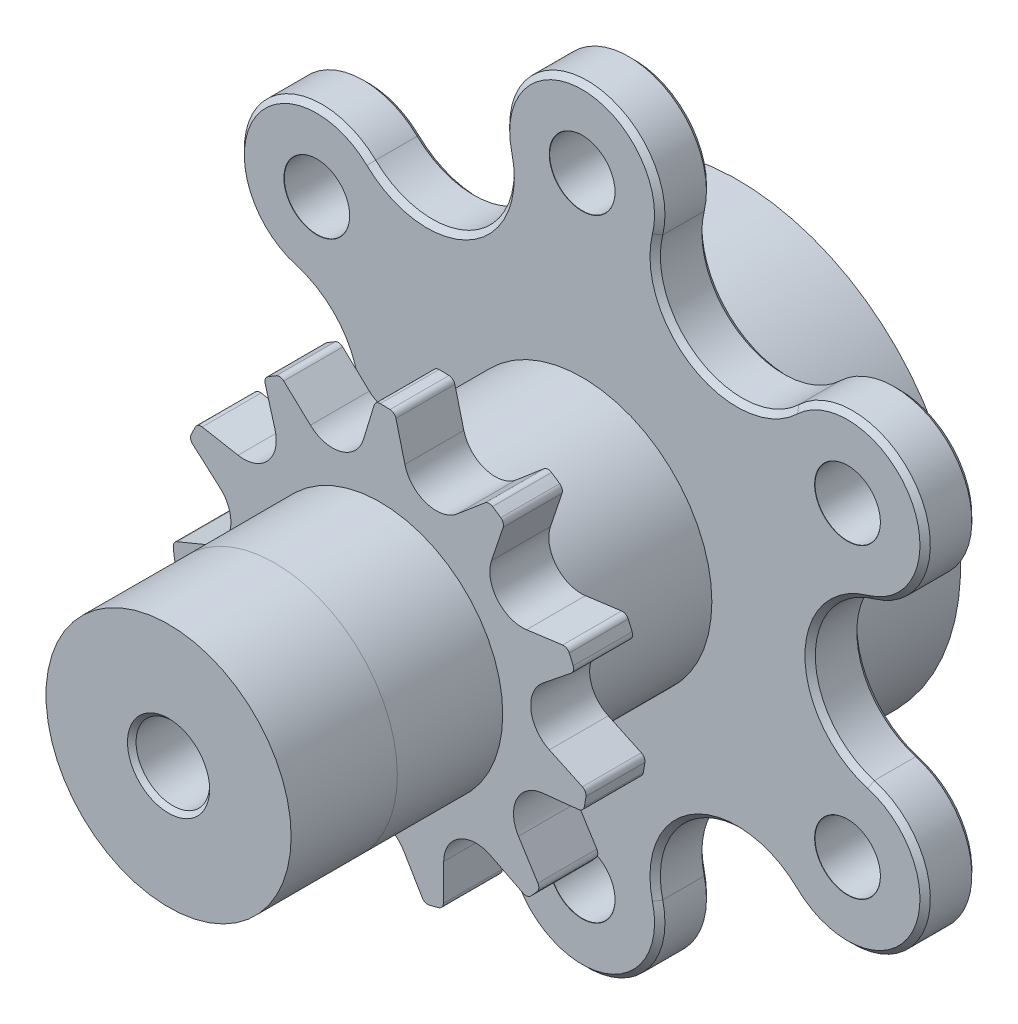
SolidWorks part; units mm, degrees
material "AISI 4130 Steel, annealed at 865C"
ref_plane "Front Plane" through (0, 0, 0) normal (0, 0, 1) x (1, 0, 0)
ref_plane "Top Plane" through (0, 0, 0) normal (0, 1, 0) x (1, 0, 0)
ref_plane "Right Plane" through (0, 0, 0) normal (1, 0, 0) x (0, 0, -1)
sketch "Sketch1" plane through (0, 0, 0) normal (0, 0, 1) x (1, 0, 0)
  circle A0 centre (0, 0) radius 47
  dimension "D1" = 94
extrude "Boss-Extrude1" add sketch "Sketch1" along normal blind 6.35
hole_wizard "Ø8.0mm Dowel Hole1" positions "Sketch3" profile "Sketch4" hole size "Ø8.0" standard "ANSI Metric" end condition through all
sketch "Sketch3" plane through (0, 0, 6.35) normal (0, 0, 1) x (1, 0, 0)
  point P0 (0, -37.5)
  dimension "D1" = 37.5
sketch "Sketch4" plane through (0, -37.5, 6.35) normal (1, 0, 0) x (0, -1, 0)
  line L0 (0, 0) -> (0, 6.35)
  line L1 (0, 6.35) -> (4, 6.35)
  line L2 (4, 6.35) -> (4, 0.025)
  line L3 (4, 0.025) -> (4.025, 0)
  line L5 (4.025, 0) -> (0, 0)
  line L6 (-4, 0.025) -> (-4.025, 0) construction
  line L11 (0, -6.35) -> (0, 107.95) construction
  dimension "Thru Hole Dia." = 8
  dimension "Thru Hole Depth" = 6.35
  dimension "Near C'Sink Dia." = 8.05
  dimension "Near C'Sink Angle" = 90
pattern_circular "CirPattern1" count 6 over 360 about axis through (0, 0, 0) along (0, 0, 1) of "Ø8.0mm Dowel Hole1"
sketch "Sketch5" plane through (0, 0, 6.35) normal (0, 0, 1) x (1, 0, 0)
  circle A0 centre (0, -37.5) radius 9.5 construction
  circle A1 centre (0, 0) radius 47 construction
  circle A2 centre (0, 0) radius 47
  circle A3 centre (-32.476, -18.75) radius 9.5 construction
  circle A4 centre (-32.476, 18.75) radius 9.5 construction
  circle A5 centre (0, 37.5) radius 9.5 construction
  circle A6 centre (32.476, 18.75) radius 9.5 construction
  circle A7 centre (32.476, -18.75) radius 9.5 construction
  circle A8 centre (0, 0) radius 27.9 construction
  arc A9 (-25.9015, 25.6076) -> (-9.2261, 35.2352) centre (-18.963, 32.8449) ccw
  arc A10 (9.2261, 35.2352) -> (25.9015, 25.6076) centre (18.963, 32.8449) ccw
  arc A11 (35.1276, 9.6276) -> (35.1276, -9.6276) centre (37.926, 0) ccw
  arc A12 (25.9015, -25.6076) -> (9.2261, -35.2352) centre (18.963, -32.8449) ccw
  arc A13 (-9.2261, -35.2352) -> (-25.9015, -25.6076) centre (-18.963, -32.8449) ccw
  arc A14 (-35.1276, -9.6276) -> (-35.1276, 9.6276) centre (-37.926, 0) ccw
  arc A15 (-9.2261, 35.2352) -> (9.2261, 35.2352) centre (0, 37.5) cw
  arc A16 (-25.9015, 25.6076) -> (-35.1276, 9.6276) centre (-32.476, 18.75) ccw
  arc A17 (-35.1276, -9.6276) -> (-25.9015, -25.6076) centre (-32.476, -18.75) ccw
  arc A18 (-9.2261, -35.2352) -> (9.2261, -35.2352) centre (0, -37.5) ccw
  arc A19 (25.9015, -25.6076) -> (35.1276, -9.6276) centre (32.476, -18.75) ccw
  arc A20 (25.9015, 25.6076) -> (35.1276, 9.6276) centre (32.476, 18.75) cw
  point P19 (0, 0)
  point P38 (0, 0)
  circle M13 centre (0, 0) radius 47
  dimension "D1" = 6
  dimension "D2" = 55.8
  dimension "D3" = 6
extrude "Cut-Extrude1" cut sketch "Sketch5" against normal through all contours A16 A9 A15 M13 | A10 A20 A2 A15 | A17 A14 A16 A2 | A18 A13 A17 M13 | A19 A12 A18 A2 | A20 A11 A19 M13
chamfer "Chamfer1" distance 0.635 angle 45 24 edges at (-40.7032, 23.5, 6.35) (-27.9, 0, 6.35) (-40.7032, -23.5, 6.35) (-13.95, -24.1621, 6.35) (0, -47, 6.35) (13.95, -24.1621, 6.35) (40.7032, -23.5, 6.35) (27.9, 0, 6.35) (40.7032, 23.5, 6.35) (13.95, 24.1621, 6.35) (0, 47, 6.35) (-13.95, 24.1621, 6.35) (0, -47, 0) (-13.95, -24.1621, 0) (13.95, -24.1621, 0) (-40.7032, -23.5, 0) (40.7032, -23.5, 0) (-27.9, 0, 0) (27.9, 0, 0) (-40.7032, 23.5, 0) (40.7032, 23.5, 0) (-13.95, 24.1621, 0) (13.95, 24.1621, 0) (0, 47, 0)
sketch "Sketch6" [suppressed] plane through (0, 0, 6.35) normal (0, 0, 1) x (1, 0, 0)
  circle A0 centre (0, 0) radius 15.875
  dimension "D1" = 31.75
extrude "Shaft" [suppressed] add sketch "Sketch6" along normal blind 53.848
sketch "Sketch7" [suppressed] plane through (0, 0, 60.198) normal (0, 0, 1) x (1, 0, 0)
  arc A0 (9.097, -5.6181) -> (9.7313, -4.4292) centre (0, 0) ccw
  arc A1 (9.097, -5.6181) -> (9.0986, -5.9863) centre (9.3955, -5.8008) ccw
  arc A2 (10.055, -4.164) -> (9.7313, -4.4292) centre (10.071, -4.5136) ccw
  arc A3 (12.1705, -3.6562) -> (12.3739, -3.4251) centre (12.0362, -3.333) ccw
  arc A4 (12.3739, -3.4251) -> (12.5248, -2.8127) centre (0.0056, -0.0518) ccw
  arc A5 (9.3895, -8.7865) -> (9.8078, -8.3144) centre (0.0056, -0.0518) ccw
  arc A6 (4.2554, -12.1469) -> (4.8452, -11.9232) centre (0.0056, -0.0518) ccw
  arc A7 (-1.8522, -12.7365) -> (-1.2261, -12.8125) centre (0.0056, -0.0518) ccw
  arc A8 (-7.5343, -10.4201) -> (-7.0152, -10.7784) centre (0.0056, -0.0518) ccw
  arc A9 (-11.489, -5.7285) -> (-11.1959, -6.287) centre (0.0056, -0.0518) ccw
  arc A10 (-12.8144, -0.0518) -> (-12.8105, -0.3671) centre (0.0056, -0.0518) ccw
  arc A11 (12.533, -2.7373) -> (12.4521, -2.5135) centre (12.183, -2.7373) ccw
  arc A12 (12.5248, -2.8127) -> (12.533, -2.7373) centre (12.183, -2.7373) ccw
  arc A13 (10.6424, -0.7555) -> (10.815, -1.0808) centre (10.9916, -0.7786) ccw
  arc A14 (10.6424, -0.7555) -> (10.6656, -0.0518) centre (0.0056, -0.0518) ccw
  arc A15 (10.6656, -0.0518) -> (10.6424, 0.6519) centre (0.0056, -0.0518) ccw
  arc A16 (10.815, 0.9772) -> (10.6424, 0.6519) centre (10.9916, 0.6751) ccw
  arc A17 (12.4521, 2.41) -> (12.533, 2.6337) centre (12.183, 2.6337) ccw
  arc A18 (-12.8105, 0.2636) -> (-12.8144, -0.0518) centre (0.0056, -0.0518) ccw
  arc A19 (-11.1959, 6.1834) -> (-11.489, 5.6249) centre (0.0056, -0.0518) ccw
  arc A20 (-7.0152, 10.6748) -> (-7.5343, 10.3165) centre (0.0056, -0.0518) ccw
  arc A21 (-1.2261, 12.7089) -> (-1.8522, 12.6329) centre (0.0056, -0.0518) ccw
  arc A22 (4.8452, 11.8197) -> (4.2554, 12.0433) centre (0.0056, -0.0518) ccw
  arc A23 (9.8078, 8.2108) -> (9.3895, 8.6829) centre (0.0056, -0.0518) ccw
  arc A24 (12.5248, 2.7091) -> (12.3739, 3.3215) centre (0.0056, -0.0518) ccw
  arc A25 (12.533, 2.6337) -> (12.5248, 2.7091) centre (12.183, 2.6337) ccw
  arc A26 (12.3739, 3.3215) -> (12.1705, 3.5526) centre (12.0362, 3.2294) ccw
  arc A27 (9.751, 4.2682) -> (10.055, 4.0604) centre (10.071, 4.4101) ccw
  arc A28 (9.751, 4.2682) -> (9.097, 5.5145) centre (0.0056, -0.0518) ccw
  arc A29 (9.0986, 5.8827) -> (9.097, 5.5145) centre (9.3955, 5.6972) ccw
  arc A30 (9.8901, 7.9852) -> (9.8078, 8.2108) centre (9.5401, 7.9852) ccw
  arc A31 (9.8824, 7.9122) -> (9.8901, 7.9852) centre (9.5401, 7.9852) ccw
  arc A32 (9.3895, 8.6829) -> (9.102, 8.793) centre (9.1333, 8.4444) ccw
  arc A33 (6.6272, 8.3023) -> (5.4688, 9.1018) centre (0.0056, -0.0518) ccw
  arc A34 (6.6272, 8.3023) -> (6.9929, 8.2596) centre (6.8446, 8.5766) ccw
  arc A35 (5.2992, 9.4287) -> (5.4688, 9.1018) centre (5.6482, 9.4024) ccw
  arc A36 (5.0501, 11.5899) -> (4.8452, 11.8197) centre (4.713, 11.4956) ccw
  arc A37 (4.2554, 12.0433) -> (3.9497, 12.0072) centre (4.1394, 11.7131) ccw
  arc A38 (1.9864, 10.4226) -> (0.5891, 10.5922) centre (0.0056, -0.0518) ccw
  arc A39 (1.9864, 10.4226) -> (2.3301, 10.5547) centre (2.0514, 10.7665) ccw
  arc A40 (0.2871, 10.8028) -> (0.5891, 10.5922) centre (0.6083, 10.9417) ccw
  arc A41 (-0.9379, 12.6007) -> (-1.2261, 12.7089) centre (-1.1925, 12.3605) ccw
  arc A42 (-1.8522, 12.6329) -> (-2.1062, 12.4588) centre (-1.8015, 12.2866) ccw
  arc A43 (-3.1082, 10.1433) -> (-4.4242, 9.6442) centre (0.0056, -0.0518) ccw
  arc A44 (-3.1082, 10.1433) -> (-2.8653, 10.42) centre (-3.2104, 10.478) ccw
  arc A45 (-4.7895, 9.6902) -> (-4.4242, 9.6442) centre (-4.5697, 9.9625) ccw
  arc A46 (-6.7097, 10.7129) -> (-7.0152, 10.6748) centre (-6.8235, 10.382) ccw
  arc A47 (-7.5343, 10.3165) -> (-7.6783, 10.0444) centre (-7.3284, 10.0335) ccw
  arc A48 (-7.4894, 7.5284) -> (-7.3855, 7.7773) centre (-7.7355, 7.7773) ccw
  arc A49 (-7.4894, 7.5284) -> (-8.4227, 6.4749) centre (0.0056, -0.0518) ccw
  arc A50 (-7.3855, 7.7773) -> (-7.4029, 7.8863) centre (-7.7355, 7.7773) ccw
  arc A51 (-8.7676, 6.3459) -> (-8.4227, 6.4749) centre (-8.6995, 6.6892) ccw
  arc A52 (-10.9431, 6.3591) -> (-11.1959, 6.1834) centre (-10.8901, 6.0132) ccw
  arc A53 (-11.489, 5.6249) -> (-11.4901, 5.3171) centre (-11.1752, 5.4699) ccw
  arc A54 (-10.1536, 3.177) -> (-10.4904, 1.8105) centre (0.0056, -0.0518) ccw
  arc A55 (-10.1372, 3.2831) -> (-10.2433, 3.5342) centre (-10.4872, 3.2831) ccw
  arc A56 (-10.1536, 3.177) -> (-10.1372, 3.2831) centre (-10.4872, 3.2831) ccw
  arc A57 (-10.7359, 1.536) -> (-10.4904, 1.8105) centre (-10.8351, 1.8716) ccw
  arc A58 (-12.6683, 0.5366) -> (-12.8105, 0.2636) centre (-12.4606, 0.255) ccw
  arc A59 (-12.8105, -0.3671) -> (-12.6683, -0.6402) centre (-12.4606, -0.3585) ccw
  arc A60 (-10.4904, -1.914) -> (-10.7359, -1.6395) centre (-10.8351, -1.9752) ccw
  arc A61 (-10.4904, -1.914) -> (-10.1536, -3.2806) centre (0.0056, -0.0518) ccw
  arc A62 (-10.1372, -3.3866) -> (-10.1536, -3.2806) centre (-10.4872, -3.3866) ccw
  arc A63 (-10.2433, -3.6377) -> (-10.1372, -3.3866) centre (-10.4872, -3.3866) ccw
  arc A64 (-11.4901, -5.4206) -> (-11.489, -5.7285) centre (-11.1752, -5.5735) ccw
  arc A65 (-11.1959, -6.287) -> (-10.9431, -6.4627) centre (-10.8901, -6.1167) ccw
  arc A66 (-8.4227, -6.5785) -> (-8.7676, -6.4495) centre (-8.6995, -6.7928) ccw
  arc A67 (-8.4227, -6.5785) -> (-7.4894, -7.632) centre (0.0056, -0.0518) ccw
  arc A68 (-7.3855, -7.8809) -> (-7.4894, -7.632) centre (-7.7355, -7.8809) ccw
  arc A69 (-7.4029, -7.9899) -> (-7.3855, -7.8809) centre (-7.7355, -7.8809) ccw
  arc A70 (-7.6783, -10.148) -> (-7.5343, -10.4201) centre (-7.3284, -10.137) ccw
  arc A71 (-7.0152, -10.7784) -> (-6.7097, -10.8165) centre (-6.8235, -10.4855) ccw
  arc A72 (-4.4242, -9.7478) -> (-4.7895, -9.7938) centre (-4.5697, -10.0661) ccw
  arc A73 (-4.4242, -9.7478) -> (-3.1082, -10.2469) centre (0.0056, -0.0518) ccw
  arc A74 (-2.8653, -10.5236) -> (-3.1082, -10.2469) centre (-3.2104, -10.5816) ccw
  arc A75 (-2.1062, -12.5624) -> (-1.8522, -12.7365) centre (-1.8015, -12.3901) ccw
  arc A76 (-1.2261, -12.8125) -> (-0.9379, -12.7043) centre (-1.1925, -12.4641) ccw
  arc A77 (0.5891, -10.6958) -> (1.9864, -10.5262) centre (0.0056, -0.0518) ccw
  arc A78 (0.5891, -10.6958) -> (0.2871, -10.9063) centre (0.6083, -11.0453) ccw
  arc A79 (2.3301, -10.6583) -> (1.9864, -10.5262) centre (2.0514, -10.8701) ccw
  arc A80 (3.9497, -12.1108) -> (4.2554, -12.1469) centre (4.1394, -11.8167) ccw
  arc A81 (4.8452, -11.9232) -> (5.0501, -11.6935) centre (4.713, -11.5991) ccw
  arc A82 (5.4688, -9.2054) -> (5.2992, -9.5322) centre (5.6482, -9.506) ccw
  arc A83 (5.4688, -9.2054) -> (6.6272, -8.4059) centre (0.0056, -0.0518) ccw
  arc A84 (6.9929, -8.3632) -> (6.6272, -8.4059) centre (6.8446, -8.6802) ccw
  arc A85 (9.102, -8.8966) -> (9.3895, -8.7865) centre (9.1333, -8.548) ccw
  arc A86 (9.8078, -8.3144) -> (9.8901, -8.0888) centre (9.5401, -8.0888) ccw
  arc A87 (9.8901, -8.0888) -> (9.8824, -8.0157) centre (9.5401, -8.0888) ccw
  circle A88 centre (0, 0) radius 15.875 construction
  circle A89 centre (0, 0) radius 15.875
  spline S0 degree 4 poles (9.0986, -5.9863) (9.1513, -6.0706) (9.2437, -6.2285) (9.367, -6.4648) (9.5091, -6.7844) (9.6282, -7.0962) (9.741, -7.4422) (9.814, -7.7129) (9.8587, -7.9047) (9.8824, -8.0157) knots 0 0 0 0 0 0.181969 0.334561 0.487154 0.639745 0.792337 1 1 1 1 1 weights 1 1 1 1 1 1 1 1 1 1
  spline S1 degree 4 poles (10.055, -4.164) (10.1544, -4.1595) (10.3368, -4.1458) (10.6013, -4.113) (10.9451, -4.0484) (11.2693, -3.9693) (11.6181, -3.8656) (11.8824, -3.7718) (12.0657, -3.6997) (12.1705, -3.6562) knots 0 0 0 0 0 0.181969 0.334561 0.487154 0.639745 0.792337 1 1 1 1 1 weights 1 1 1 1 1 1 1 1 1 1
  spline S2 degree 4 poles (10.815, -1.0808) (10.9008, -1.131) (11.056, -1.2278) (11.275, -1.3798) (11.5494, -1.5968) (11.7997, -1.8175) (12.0603, -2.0714) (12.2508, -2.2773) (12.3796, -2.4263) (12.4521, -2.5135) knots 0 0 0 0 0 0.181969 0.334561 0.487154 0.639745 0.792337 1 1 1 1 1 weights 1 1 1 1 1 1 1 1 1 1
  spline S3 degree 4 poles (10.815, 0.9772) (10.9008, 1.0274) (11.056, 1.1243) (11.275, 1.2762) (11.5494, 1.4932) (11.7997, 1.714) (12.0603, 1.9678) (12.2508, 2.1737) (12.3796, 2.3227) (12.4521, 2.41) knots 0 0 0 0 0 0.181969 0.334561 0.487154 0.639745 0.792337 1 1 1 1 1 weights 1 1 1 1 1 1 1 1 1 1
  spline S4 degree 4 poles (10.055, 4.0604) (10.1544, 4.0559) (10.3368, 4.0422) (10.6013, 4.0095) (10.9451, 3.9448) (11.2693, 3.8657) (11.6181, 3.762) (11.8824, 3.6683) (12.0657, 3.5962) (12.1705, 3.5526) knots 0 0 0 0 0 0.181969 0.334561 0.487154 0.639745 0.792337 1 1 1 1 1 weights 1 1 1 1 1 1 1 1 1 1
  spline S5 degree 4 poles (9.0986, 5.8827) (9.1513, 5.967) (9.2437, 6.1249) (9.367, 6.3612) (9.5091, 6.6809) (9.6282, 6.9927) (9.741, 7.3386) (9.814, 7.6094) (9.8587, 7.8012) (9.8824, 7.9122) knots 0 0 0 0 0 0.181969 0.334561 0.487154 0.639745 0.792337 1 1 1 1 1 weights 1 1 1 1 1 1 1 1 1 1
  spline S6 degree 4 poles (6.9929, 8.2596) (7.083, 8.3017) (7.2508, 8.3744) (7.5002, 8.4683) (7.8347, 8.5709) (8.1586, 8.6515) (8.5156, 8.7218) (8.7932, 8.7616) (8.989, 8.7829) (9.102, 8.793) knots 0 0 0 0 0 0.181969 0.334561 0.487154 0.639745 0.792337 1 1 1 1 1 weights 1 1 1 1 1 1 1 1 1 1
  spline S7 degree 4 poles (5.2992, 9.4287) (5.3067, 9.5278) (5.3151, 9.7106) (5.3144, 9.9771) (5.2917, 10.3262) (5.2522, 10.6576) (5.1914, 11.0163) (5.1302, 11.29) (5.0807, 11.4806) (5.0501, 11.5899) knots 0 0 0 0 0 0.181969 0.334561 0.487154 0.639745 0.792337 1 1 1 1 1 weights 1 1 1 1 1 1 1 1 1 1
  spline S8 degree 4 poles (2.3301, 10.5547) (2.3902, 10.6339) (2.5051, 10.7763) (2.6823, 10.9753) (2.9308, 11.2215) (3.1801, 11.4434) (3.4636, 11.6716) (3.6909, 11.8358) (3.8543, 11.9457) (3.9497, 12.0072) knots 0 0 0 0 0 0.181969 0.334561 0.487154 0.639745 0.792337 1 1 1 1 1 weights 1 1 1 1 1 1 1 1 1 1
  spline S9 degree 4 poles (0.2871, 10.8028) (0.2476, 10.8941) (0.1701, 11.0598) (0.0457, 11.2954) (-0.1366, 11.594) (-0.3256, 11.8691) (-0.5462, 12.1584) (-0.7276, 12.3723) (-0.86, 12.5181) (-0.9379, 12.6007) knots 0 0 0 0 0 0.181969 0.334561 0.487154 0.639745 0.792337 1 1 1 1 1 weights 1 1 1 1 1 1 1 1 1 1
  spline S10 degree 4 poles (-2.8653, 10.42) (-2.8488, 10.5181) (-2.8133, 10.6975) (-2.7488, 10.9561) (-2.6433, 11.2896) (-2.5256, 11.602) (-2.3806, 11.9357) (-2.2557, 12.1868) (-2.162, 12.36) (-2.1062, 12.4588) knots 0 0 0 0 0 0.181969 0.334561 0.487154 0.639745 0.792337 1 1 1 1 1 weights 1 1 1 1 1 1 1 1 1 1
  spline S11 degree 4 poles (-4.7895, 9.6902) (-4.8669, 9.7527) (-5.0125, 9.8635) (-5.2322, 10.0143) (-5.5324, 10.1939) (-5.8276, 10.3497) (-6.1574, 10.5034) (-6.4174, 10.6085) (-6.6024, 10.676) (-6.7097, 10.7129) knots 0 0 0 0 0 0.181969 0.334561 0.487154 0.639745 0.792337 1 1 1 1 1 weights 1 1 1 1 1 1 1 1 1 1
  spline S12 degree 4 poles (-7.4029, 7.8863) (-7.4339, 7.9809) (-7.4858, 8.1563) (-7.549, 8.4152) (-7.6105, 8.7595) (-7.6514, 9.0908) (-7.6782, 9.4537) (-7.6842, 9.734) (-7.6818, 9.931) (-7.6783, 10.0444) knots 0 0 0 0 0 0.181969 0.334561 0.487154 0.639745 0.792337 1 1 1 1 1 weights 1 1 1 1 1 1 1 1 1 1
  spline S13 degree 4 poles (-8.7676, 6.3459) (-8.8652, 6.3653) (-9.0456, 6.3957) (-9.3102, 6.4271) (-9.6595, 6.4467) (-9.9932, 6.4474) (-10.3567, 6.4302) (-10.6357, 6.4025) (-10.8309, 6.3763) (-10.9431, 6.3591) knots 0 0 0 0 0 0.181969 0.334561 0.487154 0.639745 0.792337 1 1 1 1 1 weights 1 1 1 1 1 1 1 1 1 1
  spline S14 degree 4 poles (-10.2433, 3.5342) (-10.3147, 3.6034) (-10.4422, 3.7346) (-10.6184, 3.9345) (-10.8329, 4.2109) (-11.0231, 4.4851) (-11.2154, 4.794) (-11.3511, 5.0395) (-11.4405, 5.215) (-11.4901, 5.3171) knots 0 0 0 0 0 0.181969 0.334561 0.487154 0.639745 0.792337 1 1 1 1 1 weights 1 1 1 1 1 1 1 1 1 1
  spline S15 degree 4 poles (-10.7359, 1.536) (-10.8312, 1.5078) (-11.0051, 1.4509) (-11.254, 1.3558) (-11.5724, 1.2107) (-11.8683, 1.0563) (-12.1821, 0.8722) (-12.4163, 0.7179) (-12.577, 0.604) (-12.6683, 0.5366) knots 0 0 0 0 0 0.181969 0.334561 0.487154 0.639745 0.792337 1 1 1 1 1 weights 1 1 1 1 1 1 1 1 1 1
  spline S16 degree 4 poles (-10.7359, -1.6395) (-10.8312, -1.6113) (-11.0051, -1.5544) (-11.254, -1.4593) (-11.5724, -1.3143) (-11.8683, -1.1599) (-12.1821, -0.9757) (-12.4163, -0.8214) (-12.577, -0.7076) (-12.6683, -0.6402) knots 0 0 0 0 0 0.181969 0.334561 0.487154 0.639745 0.792337 1 1 1 1 1 weights 1 1 1 1 1 1 1 1 1 1
  spline S17 degree 4 poles (-10.2433, -3.6377) (-10.3147, -3.707) (-10.4422, -3.8382) (-10.6184, -4.0381) (-10.8329, -4.3145) (-11.0231, -4.5887) (-11.2154, -4.8976) (-11.3511, -5.143) (-11.4405, -5.3185) (-11.4901, -5.4206) knots 0 0 0 0 0 0.181969 0.334561 0.487154 0.639745 0.792337 1 1 1 1 1 weights 1 1 1 1 1 1 1 1 1 1
  spline S18 degree 4 poles (-8.7676, -6.4495) (-8.8652, -6.4689) (-9.0456, -6.4993) (-9.3102, -6.5307) (-9.6595, -6.5503) (-9.9932, -6.551) (-10.3567, -6.5338) (-10.6357, -6.506) (-10.8309, -6.4799) (-10.9431, -6.4627) knots 0 0 0 0 0 0.181969 0.334561 0.487154 0.639745 0.792337 1 1 1 1 1 weights 1 1 1 1 1 1 1 1 1 1
  spline S19 degree 4 poles (-7.4029, -7.9899) (-7.4339, -8.0844) (-7.4858, -8.2598) (-7.549, -8.5187) (-7.6105, -8.8631) (-7.6514, -9.1944) (-7.6782, -9.5572) (-7.6842, -9.8376) (-7.6818, -10.0345) (-7.6783, -10.148) knots 0 0 0 0 0 0.181969 0.334561 0.487154 0.639745 0.792337 1 1 1 1 1 weights 1 1 1 1 1 1 1 1 1 1
  spline S20 degree 4 poles (-4.7895, -9.7938) (-4.8669, -9.8563) (-5.0125, -9.9671) (-5.2322, -10.1179) (-5.5324, -10.2975) (-5.8276, -10.4533) (-6.1574, -10.607) (-6.4174, -10.712) (-6.6024, -10.7796) (-6.7097, -10.8165) knots 0 0 0 0 0 0.181969 0.334561 0.487154 0.639745 0.792337 1 1 1 1 1 weights 1 1 1 1 1 1 1 1 1 1
  spline S21 degree 4 poles (-2.8653, -10.5236) (-2.8488, -10.6217) (-2.8133, -10.8011) (-2.7488, -11.0597) (-2.6433, -11.3932) (-2.5256, -11.7056) (-2.3806, -12.0393) (-2.2557, -12.2904) (-2.162, -12.4636) (-2.1062, -12.5624) knots 0 0 0 0 0 0.181969 0.334561 0.487154 0.639745 0.792337 1 1 1 1 1 weights 1 1 1 1 1 1 1 1 1 1
  spline S22 degree 4 poles (0.2871, -10.9063) (0.2476, -10.9976) (0.1701, -11.1634) (0.0457, -11.399) (-0.1366, -11.6976) (-0.3256, -11.9727) (-0.5462, -12.262) (-0.7276, -12.4759) (-0.86, -12.6217) (-0.9379, -12.7043) knots 0 0 0 0 0 0.181969 0.334561 0.487154 0.639745 0.792337 1 1 1 1 1 weights 1 1 1 1 1 1 1 1 1 1
  spline S23 degree 4 poles (2.3301, -10.6583) (2.3902, -10.7375) (2.5051, -10.8799) (2.6823, -11.0789) (2.9308, -11.3251) (3.1801, -11.547) (3.4636, -11.7751) (3.6909, -11.9394) (3.8543, -12.0493) (3.9497, -12.1108) knots 0 0 0 0 0 0.181969 0.334561 0.487154 0.639745 0.792337 1 1 1 1 1 weights 1 1 1 1 1 1 1 1 1 1
  spline S24 degree 4 poles (5.2992, -9.5322) (5.3067, -9.6314) (5.3151, -9.8142) (5.3144, -10.0806) (5.2917, -10.4297) (5.2522, -10.7612) (5.1914, -11.1199) (5.1302, -11.3936) (5.0807, -11.5842) (5.0501, -11.6935) knots 0 0 0 0 0 0.181969 0.334561 0.487154 0.639745 0.792337 1 1 1 1 1 weights 1 1 1 1 1 1 1 1 1 1
  spline S25 degree 4 poles (6.9929, -8.3632) (7.083, -8.4053) (7.2508, -8.478) (7.5002, -8.5719) (7.8347, -8.6744) (8.1586, -8.755) (8.5156, -8.8253) (8.7932, -8.8651) (8.989, -8.8865) (9.102, -8.8966) knots 0 0 0 0 0 0.181969 0.334561 0.487154 0.639745 0.792337 1 1 1 1 1 weights 1 1 1 1 1 1 1 1 1 1
extrude "Splines" [suppressed] cut sketch "Sketch7" against normal blind 36.348
sketch "Sketch8" [suppressed] plane through (0, 0, 60.198) normal (0, 0, 1) x (1, 0, 0)
  circle A0 centre (0, 0) radius 9.525
  circle A1 centre (0, 0) radius 14.605
  dimension "D1" = 19.05
  dimension "D2" = 29.21
extrude "Cut-Extrude3" [suppressed] cut sketch "Sketch8" against normal blind 17.272
fillet "Fillet1" [suppressed] radius 3.175
fillet "Fillet2" [suppressed] radius 2.286
chamfer "Chamfer5" [suppressed] distance 0.635 angle 45
chamfer "Chamfer6" [suppressed] distance 0.254 angle 45
hole_wizard "Tap Drill for M10x1.0 Tap3" [suppressed] positions "Sketch18" profile "Sketch19" hole size "M10x1.0" standard "ANSI Metric"
sketch "Sketch18" [suppressed] plane through (0, 0, 60.198) normal (0, 0, 1) x (1, 0, 0)
  point P0 (0, 0)
sketch "Sketch19" [suppressed] plane through (0, 0, 60.198) normal (1, 0, 0) x (0, -1, 0)
  line L0 (0, 0) -> (0, 60.198)
  line L1 (0, 60.198) -> (4.5, 60.198)
  line L2 (4.5, 60.198) -> (4.5, 0.025)
  line L3 (4.5, 0.025) -> (4.525, 0)
  line L5 (4.525, 0) -> (0, 0)
  line L6 (-4.5, 0.025) -> (-4.525, 0) construction
  line L11 (0, -6.35) -> (0, 107.95) construction
  dimension "Thru Hole Dia." = 9
  dimension "Thru Hole Depth" = 60.198
  dimension "Near C'Sink Dia." = 9.05
  dimension "Near C'Sink Angle" = 90
sketch "Sketch9" [suppressed] plane through (0, 0, 6.35) normal (0, 0, 1) x (1, 0, 0)
  circle A0 centre (0, 0) radius 15
  dimension "D1" = 30
extrude "Boss-Extrude2" [suppressed] add sketch "Sketch9" along normal blind 53.34
sketch "Sketch10" [suppressed] plane through (0, 0, 6.35) normal (0, 0, 1) x (1, 0, 0)
  circle A0 centre (0, 0) radius 15.875
  dimension "D1" = 31.75
extrude "Boss-Extrude3" [suppressed] add sketch "Sketch10" along normal blind 37.42
sketch "Sketch11" [suppressed] plane through (0, 0, 59.69) normal (0, 0, 1) x (1, 0, 0)
  arc A0 (9.097, -5.6181) -> (9.7313, -4.4292) centre (0, 0) ccw
  arc A1 (9.097, -5.6181) -> (9.0986, -5.9863) centre (9.3955, -5.8008) ccw
  arc A2 (10.055, -4.164) -> (9.7313, -4.4292) centre (10.071, -4.5136) ccw
  arc A3 (12.1705, -3.6562) -> (12.3739, -3.4251) centre (12.0362, -3.333) ccw
  arc A4 (12.3739, -3.4251) -> (12.5248, -2.8127) centre (0.0056, -0.0518) ccw
  arc A5 (9.3895, -8.7865) -> (9.8078, -8.3144) centre (0.0056, -0.0518) ccw
  arc A6 (4.2554, -12.1469) -> (4.8452, -11.9232) centre (0.0056, -0.0518) ccw
  arc A7 (-1.8522, -12.7365) -> (-1.2261, -12.8125) centre (0.0056, -0.0518) ccw
  arc A8 (-7.5343, -10.4201) -> (-7.0152, -10.7784) centre (0.0056, -0.0518) ccw
  arc A9 (-11.489, -5.7285) -> (-11.1959, -6.287) centre (0.0056, -0.0518) ccw
  arc A10 (-12.8144, -0.0518) -> (-12.8105, -0.3671) centre (0.0056, -0.0518) ccw
  arc A11 (12.533, -2.7373) -> (12.4521, -2.5135) centre (12.183, -2.7373) ccw
  arc A12 (12.5248, -2.8127) -> (12.533, -2.7373) centre (12.183, -2.7373) ccw
  arc A13 (10.6424, -0.7555) -> (10.815, -1.0808) centre (10.9916, -0.7786) ccw
  arc A14 (10.6424, -0.7555) -> (10.6656, -0.0518) centre (0.0056, -0.0518) ccw
  arc A15 (10.6656, -0.0518) -> (10.6424, 0.6519) centre (0.0056, -0.0518) ccw
  arc A16 (10.815, 0.9772) -> (10.6424, 0.6519) centre (10.9916, 0.6751) ccw
  arc A17 (12.4521, 2.41) -> (12.533, 2.6337) centre (12.183, 2.6337) ccw
  arc A18 (-12.8105, 0.2636) -> (-12.8144, -0.0518) centre (0.0056, -0.0518) ccw
  arc A19 (-11.1959, 6.1834) -> (-11.489, 5.6249) centre (0.0056, -0.0518) ccw
  arc A20 (-7.0152, 10.6748) -> (-7.5343, 10.3165) centre (0.0056, -0.0518) ccw
  arc A21 (-1.2261, 12.7089) -> (-1.8522, 12.6329) centre (0.0056, -0.0518) ccw
  arc A22 (4.8452, 11.8197) -> (4.2554, 12.0433) centre (0.0056, -0.0518) ccw
  arc A23 (9.8078, 8.2108) -> (9.3895, 8.6829) centre (0.0056, -0.0518) ccw
  arc A24 (12.5248, 2.7091) -> (12.3739, 3.3215) centre (0.0056, -0.0518) ccw
  arc A25 (12.533, 2.6337) -> (12.5248, 2.7091) centre (12.183, 2.6337) ccw
  arc A26 (12.3739, 3.3215) -> (12.1705, 3.5526) centre (12.0362, 3.2294) ccw
  arc A27 (9.751, 4.2682) -> (10.055, 4.0604) centre (10.071, 4.4101) ccw
  arc A28 (9.751, 4.2682) -> (9.097, 5.5145) centre (0.0056, -0.0518) ccw
  arc A29 (9.0986, 5.8827) -> (9.097, 5.5145) centre (9.3955, 5.6972) ccw
  arc A30 (9.8901, 7.9852) -> (9.8078, 8.2108) centre (9.5401, 7.9852) ccw
  arc A31 (9.8824, 7.9122) -> (9.8901, 7.9852) centre (9.5401, 7.9852) ccw
  arc A32 (9.3895, 8.6829) -> (9.102, 8.793) centre (9.1333, 8.4444) ccw
  arc A33 (6.6272, 8.3023) -> (5.4688, 9.1018) centre (0.0056, -0.0518) ccw
  arc A34 (6.6272, 8.3023) -> (6.9929, 8.2596) centre (6.8446, 8.5766) ccw
  arc A35 (5.2992, 9.4287) -> (5.4688, 9.1018) centre (5.6482, 9.4024) ccw
  arc A36 (5.0501, 11.5899) -> (4.8452, 11.8197) centre (4.713, 11.4956) ccw
  arc A37 (4.2554, 12.0433) -> (3.9497, 12.0072) centre (4.1394, 11.7131) ccw
  arc A38 (1.9864, 10.4226) -> (0.5891, 10.5922) centre (0.0056, -0.0518) ccw
  arc A39 (1.9864, 10.4226) -> (2.3301, 10.5547) centre (2.0514, 10.7665) ccw
  arc A40 (0.2871, 10.8028) -> (0.5891, 10.5922) centre (0.6083, 10.9417) ccw
  arc A41 (-0.9379, 12.6007) -> (-1.2261, 12.7089) centre (-1.1925, 12.3605) ccw
  arc A42 (-1.8522, 12.6329) -> (-2.1062, 12.4588) centre (-1.8015, 12.2866) ccw
  arc A43 (-3.1082, 10.1433) -> (-4.4242, 9.6442) centre (0.0056, -0.0518) ccw
  arc A44 (-3.1082, 10.1433) -> (-2.8653, 10.42) centre (-3.2104, 10.478) ccw
  arc A45 (-4.7895, 9.6902) -> (-4.4242, 9.6442) centre (-4.5697, 9.9625) ccw
  arc A46 (-6.7097, 10.7129) -> (-7.0152, 10.6748) centre (-6.8235, 10.382) ccw
  arc A47 (-7.5343, 10.3165) -> (-7.6783, 10.0444) centre (-7.3284, 10.0335) ccw
  arc A48 (-7.4894, 7.5284) -> (-7.3855, 7.7773) centre (-7.7355, 7.7773) ccw
  arc A49 (-7.4894, 7.5284) -> (-8.4227, 6.4749) centre (0.0056, -0.0518) ccw
  arc A50 (-7.3855, 7.7773) -> (-7.4029, 7.8863) centre (-7.7355, 7.7773) ccw
  arc A51 (-8.7676, 6.3459) -> (-8.4227, 6.4749) centre (-8.6995, 6.6892) ccw
  arc A52 (-10.9431, 6.3591) -> (-11.1959, 6.1834) centre (-10.8901, 6.0132) ccw
  arc A53 (-11.489, 5.6249) -> (-11.4901, 5.3171) centre (-11.1752, 5.4699) ccw
  arc A54 (-10.1536, 3.177) -> (-10.4904, 1.8105) centre (0.0056, -0.0518) ccw
  arc A55 (-10.1372, 3.2831) -> (-10.2433, 3.5342) centre (-10.4872, 3.2831) ccw
  arc A56 (-10.1536, 3.177) -> (-10.1372, 3.2831) centre (-10.4872, 3.2831) ccw
  arc A57 (-10.7359, 1.536) -> (-10.4904, 1.8105) centre (-10.8351, 1.8716) ccw
  arc A58 (-12.6683, 0.5366) -> (-12.8105, 0.2636) centre (-12.4606, 0.255) ccw
  arc A59 (-12.8105, -0.3671) -> (-12.6683, -0.6402) centre (-12.4606, -0.3585) ccw
  arc A60 (-10.4904, -1.914) -> (-10.7359, -1.6395) centre (-10.8351, -1.9752) ccw
  arc A61 (-10.4904, -1.914) -> (-10.1536, -3.2806) centre (0.0056, -0.0518) ccw
  arc A62 (-10.1372, -3.3866) -> (-10.1536, -3.2806) centre (-10.4872, -3.3866) ccw
  arc A63 (-10.2433, -3.6377) -> (-10.1372, -3.3866) centre (-10.4872, -3.3866) ccw
  arc A64 (-11.4901, -5.4206) -> (-11.489, -5.7285) centre (-11.1752, -5.5735) ccw
  arc A65 (-11.1959, -6.287) -> (-10.9431, -6.4627) centre (-10.8901, -6.1167) ccw
  arc A66 (-8.4227, -6.5785) -> (-8.7676, -6.4495) centre (-8.6995, -6.7928) ccw
  arc A67 (-8.4227, -6.5785) -> (-7.4894, -7.632) centre (0.0056, -0.0518) ccw
  arc A68 (-7.3855, -7.8809) -> (-7.4894, -7.632) centre (-7.7355, -7.8809) ccw
  arc A69 (-7.4029, -7.9899) -> (-7.3855, -7.8809) centre (-7.7355, -7.8809) ccw
  arc A70 (-7.6783, -10.148) -> (-7.5343, -10.4201) centre (-7.3284, -10.137) ccw
  arc A71 (-7.0152, -10.7784) -> (-6.7097, -10.8165) centre (-6.8235, -10.4855) ccw
  arc A72 (-4.4242, -9.7478) -> (-4.7895, -9.7938) centre (-4.5697, -10.0661) ccw
  arc A73 (-4.4242, -9.7478) -> (-3.1082, -10.2469) centre (0.0056, -0.0518) ccw
  arc A74 (-2.8653, -10.5236) -> (-3.1082, -10.2469) centre (-3.2104, -10.5816) ccw
  arc A75 (-2.1062, -12.5624) -> (-1.8522, -12.7365) centre (-1.8015, -12.3901) ccw
  arc A76 (-1.2261, -12.8125) -> (-0.9379, -12.7043) centre (-1.1925, -12.4641) ccw
  arc A77 (0.5891, -10.6958) -> (1.9864, -10.5262) centre (0.0056, -0.0518) ccw
  arc A78 (0.5891, -10.6958) -> (0.2871, -10.9063) centre (0.6083, -11.0453) ccw
  arc A79 (2.3301, -10.6583) -> (1.9864, -10.5262) centre (2.0514, -10.8701) ccw
  arc A80 (3.9497, -12.1108) -> (4.2554, -12.1469) centre (4.1394, -11.8167) ccw
  arc A81 (4.8452, -11.9232) -> (5.0501, -11.6935) centre (4.713, -11.5991) ccw
  arc A82 (5.4688, -9.2054) -> (5.2992, -9.5322) centre (5.6482, -9.506) ccw
  arc A83 (5.4688, -9.2054) -> (6.6272, -8.4059) centre (0.0056, -0.0518) ccw
  arc A84 (6.9929, -8.3632) -> (6.6272, -8.4059) centre (6.8446, -8.6802) ccw
  arc A85 (9.102, -8.8966) -> (9.3895, -8.7865) centre (9.1333, -8.548) ccw
  arc A86 (9.8078, -8.3144) -> (9.8901, -8.0888) centre (9.5401, -8.0888) ccw
  arc A87 (9.8901, -8.0888) -> (9.8824, -8.0157) centre (9.5401, -8.0888) ccw
  spline S0 degree 4 poles (9.0986, -5.9863) (9.1513, -6.0706) (9.2437, -6.2285) (9.367, -6.4648) (9.5091, -6.7844) (9.6282, -7.0962) (9.741, -7.4422) (9.814, -7.7129) (9.8587, -7.9047) (9.8824, -8.0157) knots 0 0 0 0 0 0.181969 0.334561 0.487154 0.639745 0.792337 1 1 1 1 1 weights 1 1 1 1 1 1 1 1 1 1
  spline S1 degree 4 poles (10.055, -4.164) (10.1544, -4.1595) (10.3368, -4.1458) (10.6013, -4.113) (10.9451, -4.0484) (11.2693, -3.9693) (11.6181, -3.8656) (11.8824, -3.7718) (12.0657, -3.6997) (12.1705, -3.6562) knots 0 0 0 0 0 0.181969 0.334561 0.487154 0.639745 0.792337 1 1 1 1 1 weights 1 1 1 1 1 1 1 1 1 1
  spline S2 degree 4 poles (10.815, -1.0808) (10.9008, -1.131) (11.056, -1.2278) (11.275, -1.3798) (11.5494, -1.5968) (11.7997, -1.8175) (12.0603, -2.0714) (12.2508, -2.2773) (12.3796, -2.4263) (12.4521, -2.5135) knots 0 0 0 0 0 0.181969 0.334561 0.487154 0.639745 0.792337 1 1 1 1 1 weights 1 1 1 1 1 1 1 1 1 1
  spline S3 degree 4 poles (10.815, 0.9772) (10.9008, 1.0274) (11.056, 1.1243) (11.275, 1.2762) (11.5494, 1.4932) (11.7997, 1.714) (12.0603, 1.9678) (12.2508, 2.1737) (12.3796, 2.3227) (12.4521, 2.41) knots 0 0 0 0 0 0.181969 0.334561 0.487154 0.639745 0.792337 1 1 1 1 1 weights 1 1 1 1 1 1 1 1 1 1
  spline S4 degree 4 poles (10.055, 4.0604) (10.1544, 4.0559) (10.3368, 4.0422) (10.6013, 4.0095) (10.9451, 3.9448) (11.2693, 3.8657) (11.6181, 3.762) (11.8824, 3.6683) (12.0657, 3.5962) (12.1705, 3.5526) knots 0 0 0 0 0 0.181969 0.334561 0.487154 0.639745 0.792337 1 1 1 1 1 weights 1 1 1 1 1 1 1 1 1 1
  spline S5 degree 4 poles (9.0986, 5.8827) (9.1513, 5.967) (9.2437, 6.1249) (9.367, 6.3612) (9.5091, 6.6809) (9.6282, 6.9927) (9.741, 7.3386) (9.814, 7.6094) (9.8587, 7.8012) (9.8824, 7.9122) knots 0 0 0 0 0 0.181969 0.334561 0.487154 0.639745 0.792337 1 1 1 1 1 weights 1 1 1 1 1 1 1 1 1 1
  spline S6 degree 4 poles (6.9929, 8.2596) (7.083, 8.3017) (7.2508, 8.3744) (7.5002, 8.4683) (7.8347, 8.5709) (8.1586, 8.6515) (8.5156, 8.7218) (8.7932, 8.7616) (8.989, 8.7829) (9.102, 8.793) knots 0 0 0 0 0 0.181969 0.334561 0.487154 0.639745 0.792337 1 1 1 1 1 weights 1 1 1 1 1 1 1 1 1 1
  spline S7 degree 4 poles (5.2992, 9.4287) (5.3067, 9.5278) (5.3151, 9.7106) (5.3144, 9.9771) (5.2917, 10.3262) (5.2522, 10.6576) (5.1914, 11.0163) (5.1302, 11.29) (5.0807, 11.4806) (5.0501, 11.5899) knots 0 0 0 0 0 0.181969 0.334561 0.487154 0.639745 0.792337 1 1 1 1 1 weights 1 1 1 1 1 1 1 1 1 1
  spline S8 degree 4 poles (2.3301, 10.5547) (2.3902, 10.6339) (2.5051, 10.7763) (2.6823, 10.9753) (2.9308, 11.2215) (3.1801, 11.4434) (3.4636, 11.6716) (3.6909, 11.8358) (3.8543, 11.9457) (3.9497, 12.0072) knots 0 0 0 0 0 0.181969 0.334561 0.487154 0.639745 0.792337 1 1 1 1 1 weights 1 1 1 1 1 1 1 1 1 1
  spline S9 degree 4 poles (0.2871, 10.8028) (0.2476, 10.8941) (0.1701, 11.0598) (0.0457, 11.2954) (-0.1366, 11.594) (-0.3256, 11.8691) (-0.5462, 12.1584) (-0.7276, 12.3723) (-0.86, 12.5181) (-0.9379, 12.6007) knots 0 0 0 0 0 0.181969 0.334561 0.487154 0.639745 0.792337 1 1 1 1 1 weights 1 1 1 1 1 1 1 1 1 1
  spline S10 degree 4 poles (-2.8653, 10.42) (-2.8488, 10.5181) (-2.8133, 10.6975) (-2.7488, 10.9561) (-2.6433, 11.2896) (-2.5256, 11.602) (-2.3806, 11.9357) (-2.2557, 12.1868) (-2.162, 12.36) (-2.1062, 12.4588) knots 0 0 0 0 0 0.181969 0.334561 0.487154 0.639745 0.792337 1 1 1 1 1 weights 1 1 1 1 1 1 1 1 1 1
  spline S11 degree 4 poles (-4.7895, 9.6902) (-4.8669, 9.7527) (-5.0125, 9.8635) (-5.2322, 10.0143) (-5.5324, 10.1939) (-5.8276, 10.3497) (-6.1574, 10.5034) (-6.4174, 10.6085) (-6.6024, 10.676) (-6.7097, 10.7129) knots 0 0 0 0 0 0.181969 0.334561 0.487154 0.639745 0.792337 1 1 1 1 1 weights 1 1 1 1 1 1 1 1 1 1
  spline S12 degree 4 poles (-7.4029, 7.8863) (-7.4339, 7.9809) (-7.4858, 8.1563) (-7.549, 8.4152) (-7.6105, 8.7595) (-7.6514, 9.0908) (-7.6782, 9.4537) (-7.6842, 9.734) (-7.6818, 9.931) (-7.6783, 10.0444) knots 0 0 0 0 0 0.181969 0.334561 0.487154 0.639745 0.792337 1 1 1 1 1 weights 1 1 1 1 1 1 1 1 1 1
  spline S13 degree 4 poles (-8.7676, 6.3459) (-8.8652, 6.3653) (-9.0456, 6.3957) (-9.3102, 6.4271) (-9.6595, 6.4467) (-9.9932, 6.4474) (-10.3567, 6.4302) (-10.6357, 6.4025) (-10.8309, 6.3763) (-10.9431, 6.3591) knots 0 0 0 0 0 0.181969 0.334561 0.487154 0.639745 0.792337 1 1 1 1 1 weights 1 1 1 1 1 1 1 1 1 1
  spline S14 degree 4 poles (-10.2433, 3.5342) (-10.3147, 3.6034) (-10.4422, 3.7346) (-10.6184, 3.9345) (-10.8329, 4.2109) (-11.0231, 4.4851) (-11.2154, 4.794) (-11.3511, 5.0395) (-11.4405, 5.215) (-11.4901, 5.3171) knots 0 0 0 0 0 0.181969 0.334561 0.487154 0.639745 0.792337 1 1 1 1 1 weights 1 1 1 1 1 1 1 1 1 1
  spline S15 degree 4 poles (-10.7359, 1.536) (-10.8312, 1.5078) (-11.0051, 1.4509) (-11.254, 1.3558) (-11.5724, 1.2107) (-11.8683, 1.0563) (-12.1821, 0.8722) (-12.4163, 0.7179) (-12.577, 0.604) (-12.6683, 0.5366) knots 0 0 0 0 0 0.181969 0.334561 0.487154 0.639745 0.792337 1 1 1 1 1 weights 1 1 1 1 1 1 1 1 1 1
  spline S16 degree 4 poles (-10.7359, -1.6395) (-10.8312, -1.6113) (-11.0051, -1.5544) (-11.254, -1.4593) (-11.5724, -1.3143) (-11.8683, -1.1599) (-12.1821, -0.9757) (-12.4163, -0.8214) (-12.577, -0.7076) (-12.6683, -0.6402) knots 0 0 0 0 0 0.181969 0.334561 0.487154 0.639745 0.792337 1 1 1 1 1 weights 1 1 1 1 1 1 1 1 1 1
  spline S17 degree 4 poles (-10.2433, -3.6377) (-10.3147, -3.707) (-10.4422, -3.8382) (-10.6184, -4.0381) (-10.8329, -4.3145) (-11.0231, -4.5887) (-11.2154, -4.8976) (-11.3511, -5.143) (-11.4405, -5.3185) (-11.4901, -5.4206) knots 0 0 0 0 0 0.181969 0.334561 0.487154 0.639745 0.792337 1 1 1 1 1 weights 1 1 1 1 1 1 1 1 1 1
  spline S18 degree 4 poles (-8.7676, -6.4495) (-8.8652, -6.4689) (-9.0456, -6.4993) (-9.3102, -6.5307) (-9.6595, -6.5503) (-9.9932, -6.551) (-10.3567, -6.5338) (-10.6357, -6.506) (-10.8309, -6.4799) (-10.9431, -6.4627) knots 0 0 0 0 0 0.181969 0.334561 0.487154 0.639745 0.792337 1 1 1 1 1 weights 1 1 1 1 1 1 1 1 1 1
  spline S19 degree 4 poles (-7.4029, -7.9899) (-7.4339, -8.0844) (-7.4858, -8.2598) (-7.549, -8.5187) (-7.6105, -8.8631) (-7.6514, -9.1944) (-7.6782, -9.5572) (-7.6842, -9.8376) (-7.6818, -10.0345) (-7.6783, -10.148) knots 0 0 0 0 0 0.181969 0.334561 0.487154 0.639745 0.792337 1 1 1 1 1 weights 1 1 1 1 1 1 1 1 1 1
  spline S20 degree 4 poles (-4.7895, -9.7938) (-4.8669, -9.8563) (-5.0125, -9.9671) (-5.2322, -10.1179) (-5.5324, -10.2975) (-5.8276, -10.4533) (-6.1574, -10.607) (-6.4174, -10.712) (-6.6024, -10.7796) (-6.7097, -10.8165) knots 0 0 0 0 0 0.181969 0.334561 0.487154 0.639745 0.792337 1 1 1 1 1 weights 1 1 1 1 1 1 1 1 1 1
  spline S21 degree 4 poles (-2.8653, -10.5236) (-2.8488, -10.6217) (-2.8133, -10.8011) (-2.7488, -11.0597) (-2.6433, -11.3932) (-2.5256, -11.7056) (-2.3806, -12.0393) (-2.2557, -12.2904) (-2.162, -12.4636) (-2.1062, -12.5624) knots 0 0 0 0 0 0.181969 0.334561 0.487154 0.639745 0.792337 1 1 1 1 1 weights 1 1 1 1 1 1 1 1 1 1
  spline S22 degree 4 poles (0.2871, -10.9063) (0.2476, -10.9976) (0.1701, -11.1634) (0.0457, -11.399) (-0.1366, -11.6976) (-0.3256, -11.9727) (-0.5462, -12.262) (-0.7276, -12.4759) (-0.86, -12.6217) (-0.9379, -12.7043) knots 0 0 0 0 0 0.181969 0.334561 0.487154 0.639745 0.792337 1 1 1 1 1 weights 1 1 1 1 1 1 1 1 1 1
  spline S23 degree 4 poles (2.3301, -10.6583) (2.3902, -10.7375) (2.5051, -10.8799) (2.6823, -11.0789) (2.9308, -11.3251) (3.1801, -11.547) (3.4636, -11.7751) (3.6909, -11.9394) (3.8543, -12.0493) (3.9497, -12.1108) knots 0 0 0 0 0 0.181969 0.334561 0.487154 0.639745 0.792337 1 1 1 1 1 weights 1 1 1 1 1 1 1 1 1 1
  spline S24 degree 4 poles (5.2992, -9.5322) (5.3067, -9.6314) (5.3151, -9.8142) (5.3144, -10.0806) (5.2917, -10.4297) (5.2522, -10.7612) (5.1914, -11.1199) (5.1302, -11.3936) (5.0807, -11.5842) (5.0501, -11.6935) knots 0 0 0 0 0 0.181969 0.334561 0.487154 0.639745 0.792337 1 1 1 1 1 weights 1 1 1 1 1 1 1 1 1 1
  spline S25 degree 4 poles (6.9929, -8.3632) (7.083, -8.4053) (7.2508, -8.478) (7.5002, -8.5719) (7.8347, -8.6744) (8.1586, -8.755) (8.5156, -8.8253) (8.7932, -8.8651) (8.989, -8.8865) (9.102, -8.8966) knots 0 0 0 0 0 0.181969 0.334561 0.487154 0.639745 0.792337 1 1 1 1 1 weights 1 1 1 1 1 1 1 1 1 1
extrude "Boss-Extrude4" [suppressed] add sketch "Sketch11" along normal blind 19.05
fillet "Fillet3" [suppressed] radius 2.54
chamfer "Chamfer3" [suppressed] distance 0.254 angle 45
chamfer "Chamfer4" [suppressed] distance 0.635 angle 45
hole_wizard "Tap Drill for M10x1.0 Tap2" [suppressed] positions "Sketch16" profile "Sketch17" hole size "M10x1.0" standard "ANSI Metric"
sketch "Sketch16" [suppressed] plane through (0, 0, 78.74) normal (0, 0, 1) x (1, 0, 0)
  point P0 (0, 0)
sketch "Sketch17" [suppressed] plane through (0, 0, 78.74) normal (1, 0, 0) x (0, -1, 0)
  line L0 (0, 0) -> (0, 78.74)
  line L1 (0, 78.74) -> (4.5, 78.74)
  line L2 (4.5, 78.74) -> (4.5, 0.025)
  line L3 (4.5, 0.025) -> (4.525, 0)
  line L5 (4.525, 0) -> (0, 0)
  line L6 (-4.5, 0.025) -> (-4.525, 0) construction
  line L11 (0, -6.35) -> (0, 107.95) construction
  dimension "Thru Hole Dia." = 9
  dimension "Thru Hole Depth" = 78.74
  dimension "Near C'Sink Dia." = 9.05
  dimension "Near C'Sink Angle" = 90
sketch "Sketch20" plane through (0, 0, 0) normal (0, 0, -1) x (-1, 0, 0)
  circle A0 centre (0, 0) radius 27.265
  circle A2 centre (0, 0) radius 23.455
  dimension "D1" = 54.53
  dimension "D2" = 3.81
extrude "Boss-Extrude5" add sketch "Sketch20" along normal blind 12.7
sketch "Sketch21" plane through (0, 0, 6.35) normal (0, 0, 1) x (1, 0, 0)
  circle A0 centre (0, 0) radius 15.875
  dimension "D1" = 31.75
extrude "Boss-Extrude6" add sketch "Sketch21" along normal blind 17.5
sketch "Sketch22" plane through (0, 0, 23.85) normal (0, 0, 1) x (1, 0, 0)
  circle A0 centre (0, 0) radius 27.5082
  dimension "D1" = 55.0164
extrude "Boss-Extrude7" add sketch "Sketch22" along normal blind 7.2136
sketch "Sketch25" plane through (0, 0, 31.0636) normal (0, 0, 1) x (1, 0, 0)
  line L3 (-0.7438, 24.8872) -> (-2.0441, 20.6195)
  line L4 (-5.8344, 21.7744) -> (0, 0) construction
  line L5 (-11.7995, 21.9248) -> (-8.5396, 18.8791)
  circle A4 centre (0, 0) radius 27.5082 construction
  circle A5 centre (0, 0) radius 27.5082
  arc A6 (0, 25.4381) -> (-0.7438, 24.8872) centre (0, 24.6606) ccw
  arc A7 (-12.7191, 22.03) -> (-11.7995, 21.9248) centre (-12.3303, 21.3567) cw
  arc A8 (-2.0441, 20.6195) -> (-8.5396, 18.8791) centre (-5.8344, 21.7744) cw
  arc A9 (0, 25.4381) -> (-12.7191, 22.03) centre (0, 0) ccw
  circle A10 centre (0, 0) radius 25.4381
  dimension "D2" = 22.5425
  dimension "D4" = 6.4959
  dimension "D5" = 2.8862
  dimension "D1" = 50.8762
  dimension "D6" = 3.9624
  dimension "D3" = 5.8344
  dimension "D7" = 4.2677
  dimension "D8" = 3.0458
extrude "Cut-Extrude4" cut sketch "Sketch25" against normal blind 7.62
pattern_circular "CirPattern2" count 11 over 360 about axis through (0, 0, 0) along (0, 0, 1) of "Cut-Extrude4"
sketch "Sketch23" plane through (0, 0, 31.0636) normal (0, 0, 1) x (1, 0, 0)
  circle A1 centre (0, 0) radius 15
  dimension "D1" = 30
extrude "Boss-Extrude8" add sketch "Sketch23" along normal blind 25.9
ref_plane "Plane2" through (0, 15, 0) normal (0, 1, 0) x (1, 0, 0)
sketch "Sketch27" plane through (0, 15, 0) normal (0, 1, 0) x (1, 0, 0)
  line L0 (-15, -43.9636) -> (15, -43.9636)
  line L1 (-15, -56.9636) -> (15, -56.9636) construction
  line L2 (-15, -56.9636) -> (15, -56.9636) construction
  dimension "D1" = 13
split line "Split Line3"
hole_wizard "M10x1.0 Tapped Hole1" positions "Sketch28" profile "Sketch29" tap size "M10x1.0" standard "ANSI Metric" end condition through all
sketch "Sketch28" plane through (0, 0, 56.9636) normal (0, 0, 1) x (1, 0, 0)
  point P0 (0, 0)
sketch "Sketch29" plane through (0, 0, 56.9636) normal (1, 0, 0) x (0, -1, 0)
  line L0 (0, 0) -> (0, 69.6636)
  line L1 (0, 69.6636) -> (4.5, 69.6636)
  line L2 (4.5, 69.6636) -> (4.5, 0.525)
  line L3 (4.5, 0.525) -> (5.025, 0)
  line L5 (5.025, 0) -> (0, 0)
  line L6 (-4.5, 0.525) -> (-5.025, 0) construction
  line L11 (0, -6.35) -> (0, 107.95) construction
  dimension "Thru Tap Drill Dia." = 9
  dimension "Thru Tap Drill Depth" = 69.6636
  dimension "Near C'Sink Dia." = 10.05
  dimension "Near C'Sink Angle" = 90
ref_plane "Plane3" through (0, 0, 27.4568) normal (0, 0, 1) x (1, 0, 0)
sketch "Sketch30" plane through (0, 0, 27.4568) normal (0, 0, 1) x (1, 0, 0)
  circle A0 centre (0, 0) radius 22.5425 construction
  dimension "D1" = 45.085
